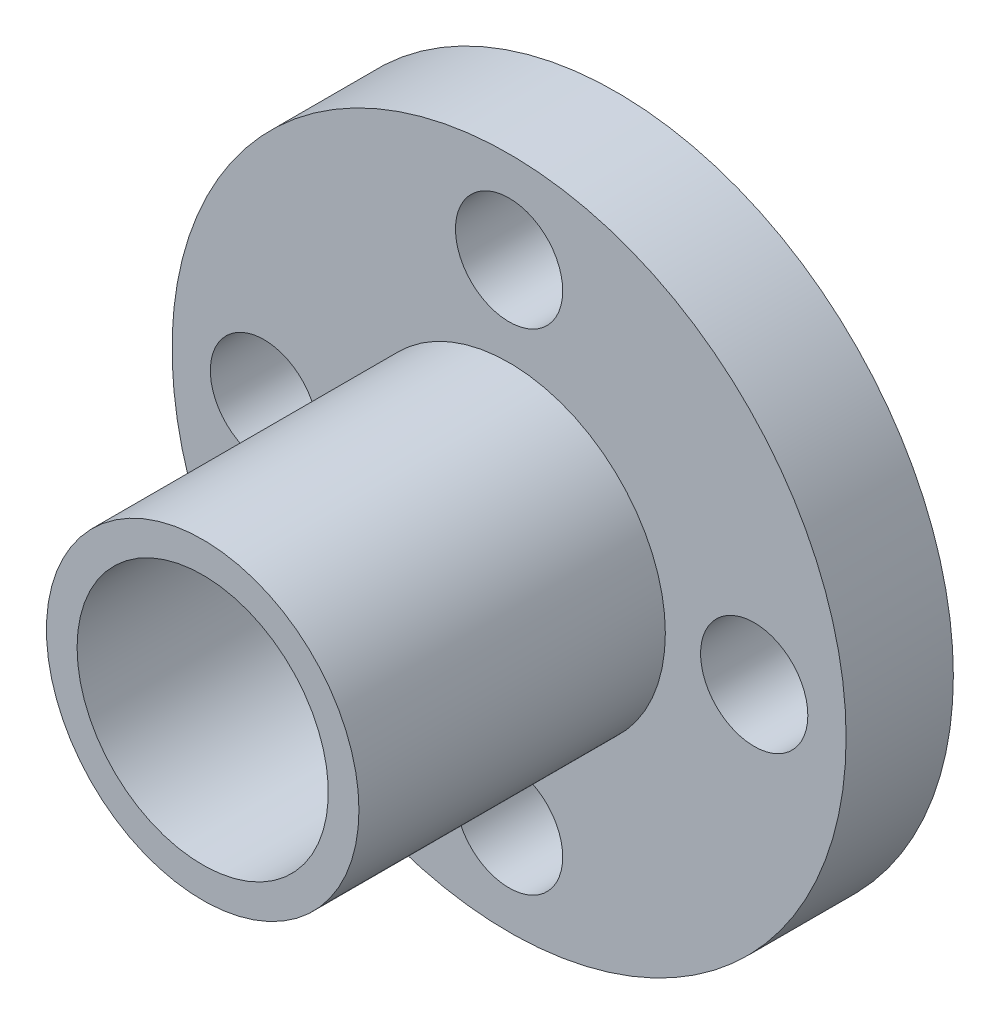
SolidWorks part; units mm, degrees
material "Brass"
ref_plane "Front Plane" through (0, 0, 0) normal (0, 0, 1) x (1, 0, 0)
ref_plane "Top Plane" through (0, 0, 0) normal (0, 1, 0) x (1, 0, 0)
ref_plane "Right Plane" through (0, 0, 0) normal (1, 0, 0) x (0, 0, -1)
sketch "Sketch1" plane through (0, 0, 0) normal (0, 0, 1) x (1, 0, 0)
  circle A0 centre (0, 0) radius 5.1
  dimension "D1" = 10.2
extrude "Boss-Extrude1" add sketch "Sketch1" along normal blind 15
ref_plane "Plane1" through (0, 0, 1.5) normal (0, 0, 1) x (1, 0, 0)
sketch "Sketch2" plane through (0, 0, 1.5) normal (0, 0, 1) x (1, 0, 0)
  circle A0 centre (0, 0) radius 11
  circle A1 centre (0, 0) radius 8 construction
  circle A2 centre (0, 8) radius 1.75
  circle A3 centre (8, 0) radius 1.75
  circle A4 centre (0, -8) radius 1.75
  circle A5 centre (-8, 0) radius 1.75
  point P15 (0, 0)
  dimension "D1" = 22
  dimension "D2" = 16
  dimension "D3" = 3.5
  dimension "D4" = 4
extrude "Boss-Extrude2" add sketch "Sketch2" along normal blind 3.5
sketch "Sketch3" plane through (0, 0, 0) normal (0, 0, -1) x (-1, 0, 0)
  circle A0 centre (0, 0) radius 4.1
  dimension "D1" = 8.2
extrude "Cut-Extrude1" cut sketch "Sketch3" against normal through all
